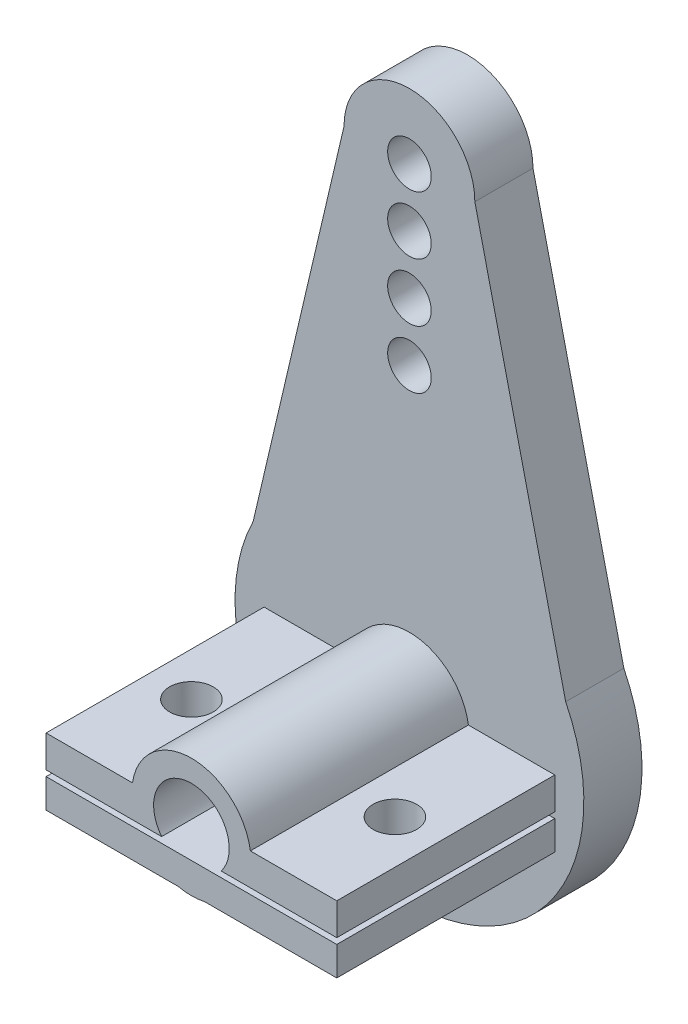
SolidWorks part; units mm, degrees
ref_plane "Płaszczyzna przednia" through (0, 0, 0) normal (0, 0, 1) x (1, 0, 0)
ref_plane "Płaszczyzna górna" through (0, 0, 0) normal (0, 1, 0) x (1, 0, 0)
ref_plane "Płaszczyzna prawa" through (0, 0, 0) normal (1, 0, 0) x (0, 0, -1)
sketch "Szkic1" plane through (0, 0, 0) normal (0, 0, 1) x (1, 0, 0)
  circle A0 centre (0, 0) radius 12
  circle A1 centre (0, 32) radius 4.5
  point P5 (0, 0)
extrude "Dodanie-wyciągnięcie2" add sketch "Szkic1" along normal blind 4
sketch "Szkic2" plane through (0, 0, 0) normal (0, 0, -1) x (-1, 0, 0)
  line L0 (-4.5, 32) -> (-12, 0)
  line L4 (12, 0) -> (4.5, 32)
  line L5 (4.5, 32) -> (-4.5, 32)
  line L6 (12, 0) -> (-12, 0)
  circle A0 centre (0, 32) radius 4.5 construction
  circle A1 centre (0, 0) radius 12 construction
  point P6 (0, 0)
  point P7 (0, 0)
  point P8 (0, 0)
  point P9 (0, 0)
  point P10 (0, 0)
extrude "Dodanie-wyciągnięcie3" add sketch "Szkic2" against normal blind 4
sketch "Szkic3" plane through (0, 0, 0) normal (0, 0, -1) x (-1, 0, 0)
  circle A0 centre (0, 32) radius 1.5
  circle A1 centre (0, 28) radius 1.5
  circle A4 centre (0, 24) radius 1.5
  circle A6 centre (0, 20) radius 1.5
  point P6 (0, 0)
  point P7 (0, 0)
  point P10 (0, 0)
  point P11 (0, 0)
  point P12 (0, 0)
  point P13 (0, 0)
  point P14 (0, 0)
  point P15 (0, 0)
  point P16 (0, 0)
  point P17 (0, 0)
  point P18 (0, 0)
extrude "Wytnij-wyciągnięcie1" cut sketch "Szkic3" against normal up to next
sketch "Szkic4" plane through (0, 0, 4) normal (0, 0, 1) x (1, 0, 0)
  circle A0 centre (0, 0) radius 2.6
  circle A2 centre (0, 0) radius 4.1
extrude "Dodanie-wyciągnięcie4" add sketch "Szkic4" along normal blind 15
sketch "Szkic5" plane through (0, 0, 4) normal (0, 0, 1) x (1, 0, 0)
  line L1 (-10, -2) -> (10, -2)
  line L2 (-10, -2) -> (-10, -4)
  line L3 (-10, -4) -> (10, -4)
  line L4 (10, -2) -> (10, -4)
extrude "Dodanie-wyciągnięcie5" add sketch "Szkic5" along normal blind 15
sketch "Szkic6" plane through (0, 0, 4) normal (0, 0, 1) x (1, 0, 0)
  line L1 (-10, -2) -> (6, -2)
  line L2 (-10, -2) -> (-10, -1.6)
  line L3 (-10, -1.6) -> (6, -1.6)
  line L4 (6, -2) -> (6, -1.6)
extrude "Wytnij-wyciągnięcie2" cut sketch "Szkic6" along normal blind 15
sketch "Szkic7" plane through (0, 0, 4) normal (0, 0, 1) x (1, 0, 0)
  line L0 (-2.0494, -1.6) -> (-3.7749, -1.6) construction
  line L1 (-3.0448, -1.6) -> (-10, -1.6)
  line L2 (-3.0448, -1.6) -> (-3.0448, 0.6)
  line L3 (-3.0448, 0.6) -> (-10, 0.6)
  line L4 (-10, -1.6) -> (-10, 0.6)
  line L6 (3.3541, -1.6) -> (10, -1.6)
  line L7 (3.3541, -1.6) -> (3.3541, 0.6)
  line L8 (3.3541, 0.6) -> (10, 0.6)
  line L9 (10, -1.6) -> (10, 0.6)
extrude "Dodanie-wyciągnięcie6" add sketch "Szkic7" along normal blind 15
sketch "Szkic10" plane through (0, 0.6, 0) normal (0, 1, 0) x (1, 0, 0)
  circle A0 centre (-7, -12) radius 1.5
  circle A1 centre (7, -12) radius 1.5
extrude "Wytnij-wyciągnięcie4" cut sketch "Szkic10" against normal blind 5
